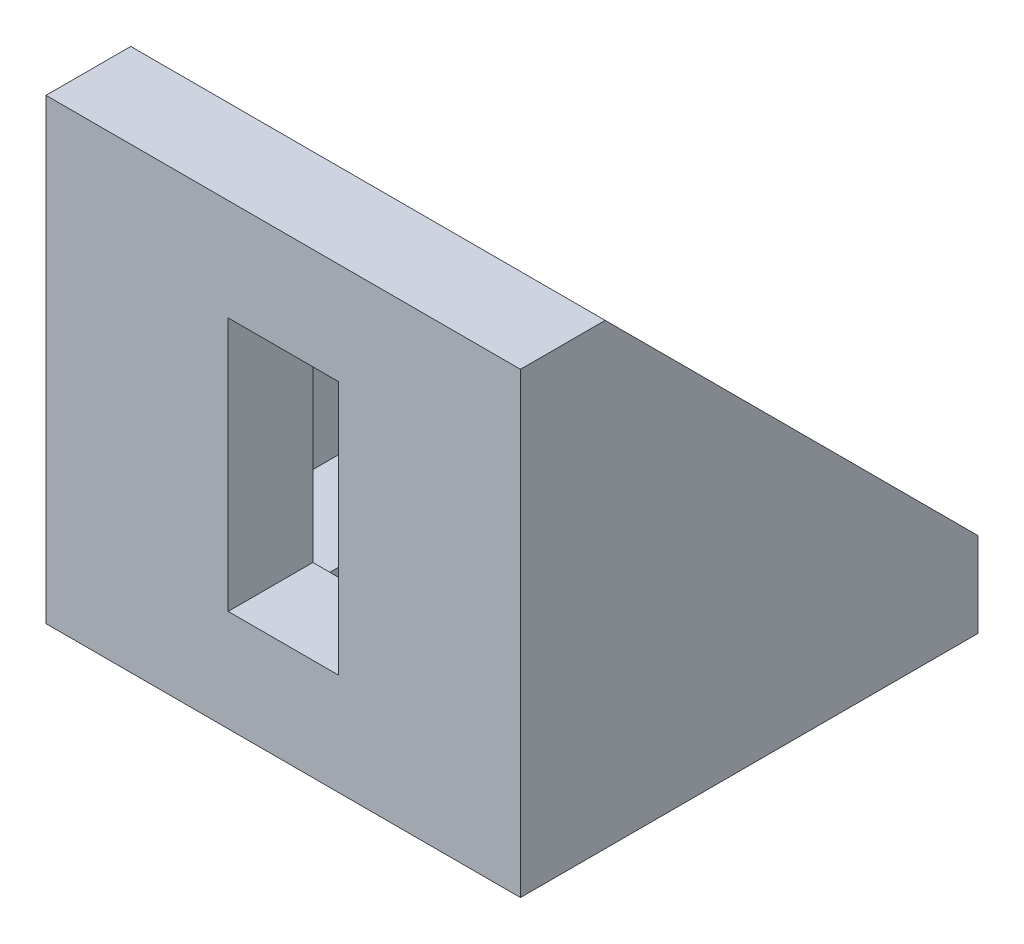
SolidWorks part; units mm, degrees
ref_plane "Top Plane" through (0, 0, 0) normal (0, 0, 1) x (1, 0, 0)
ref_plane "Right Plane" through (0, 0, 0) normal (0, 1, 0) x (1, 0, 0)
ref_plane "Front Plane" through (0, 0, 0) normal (1, 0, 0) x (0, 0, -1)
sketch "Sketch1" plane through (0, 0, 0) normal (1, 0, 0) x (0, 0, -1)
  line L0 (0, 0) -> (18, 0)
  line L1 (18, 0) -> (18, 3.3333)
  line L2 (18, 3.3333) -> (10.6667, 10.6667)
  line L3 (10.6667, 10.6667) -> (0, 0)
  dimension "D1" = 45
  dimension "var1" = 18
  dimension "D2" = 3.3333
extrude "Boss-Extrude1" add sketch "Sketch1" along normal mid plane 18.6667
sketch "Sketch2" plane through (0, 0, 0) normal (0, -1, 0) x (1, 0, 0)
  line L0 (9.3333, -18) -> (-9.3333, -18) construction
  line L1 (6, -18) -> (-6, -18)
  line L2 (6, -18) -> (6, -3.3333)
  line L3 (6, -3.3333) -> (-6, -3.3333)
  line L4 (-6, -18) -> (-6, -3.3333)
  line L5 (6, -3.3333) -> (6, 0) construction
  line L6 (9.3333, 0) -> (-9.3333, 0) construction
  line L8 (9.3333, 0) -> (9.3333, -18) construction
  line L9 (9.3333, -3.3333) -> (6, -3.3333) construction
  point P6 (0, -18)
  dimension "D1" = 3.3333
extrude "Cut-Extrude1" cut sketch "Sketch2" against normal blind 28 from vertex at -3.3333 starting at point (9.3333, 3.3333, -18)
sketch "Sketch3" plane through (0, 0, 0) normal (0, -1, 0) x (1, 0, 0)
  line L0 (0, -18) -> (0, -14) construction
  line L1 (2.1667, -14) -> (-2.1667, -14)
  line L2 (2.1667, -14) -> (2.1667, -4)
  line L3 (2.1667, -4) -> (-2.1667, -4)
  line L4 (-2.1667, -14) -> (-2.1667, -4)
  line L5 (9.3333, -18) -> (-9.3333, -18) construction
  line L6 (0, -4) -> (0, 0) construction
  line L7 (9.3333, 0) -> (-9.3333, 0) construction
  dimension "D1" = 4.3333
  dimension "D2" = 4
extrude "Cut-Extrude2" cut sketch "Sketch3" against normal through all
mirror "Mirror1" about plane through (9.3333, 10.6667, -10.6667) normal (0, -0.7071, -0.7071) of bodies 104
equation "\"D2@Sketch1\"=\"var1\"*5/27"
equation "\"D1@Boss-Extrude1\"=\"var1\"*28/27"
equation "\"D1@Sketch2\"=\"var1\"*5/27"
equation "\"D1@Sketch3\"=\"var1\"*6.5/27"
equation "\"D2@Sketch3\"=\"var1\"*6/27"
